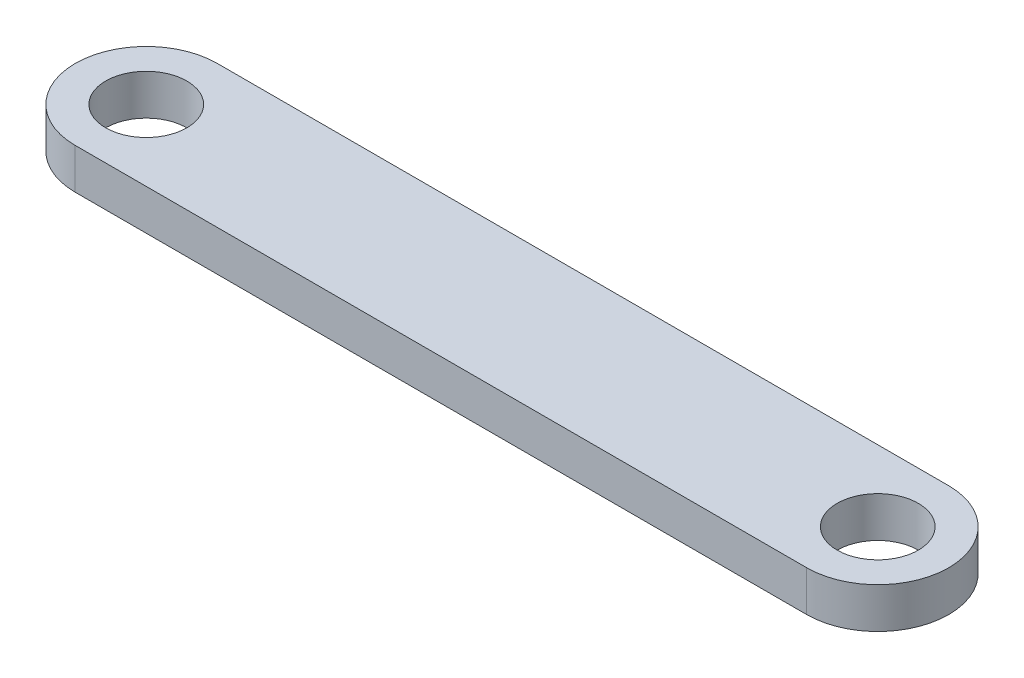
SolidWorks part; units mm, degrees
ref_plane "Front Plane" through (0, 0, 0) normal (0, 0, 1) x (1, 0, 0)
ref_plane "Top Plane" through (0, 0, 0) normal (0, 1, 0) x (1, 0, 0)
ref_plane "Right Plane" through (0, 0, 0) normal (1, 0, 0) x (0, 0, -1)
sketch "Sketch2" plane through (0, 0, 0) normal (0, 1, 0) x (1, 0, 0)
  line L0 (-26.6607, 9.9614) -> (9.3893, 9.9614)
  line L1 (-26.6607, 2.9614) -> (9.3893, 2.9614)
  circle A0 centre (-26.6607, 6.4614) radius 2
  circle A1 centre (9.3893, 6.4614) radius 2
  arc A2 (-26.6607, 9.9614) -> (-26.6607, 2.9614) centre (-26.6607, 6.4614) ccw
  arc A3 (9.3893, 2.9614) -> (9.3893, 9.9614) centre (9.3893, 6.4614) ccw
  dimension "D1" = 4
  dimension "D2" = 4
  dimension "D3" = 7
  dimension "D4" = 7
  dimension "D5" = 36.05
extrude "Boss-Extrude1" add sketch "Sketch2" along normal blind 2
